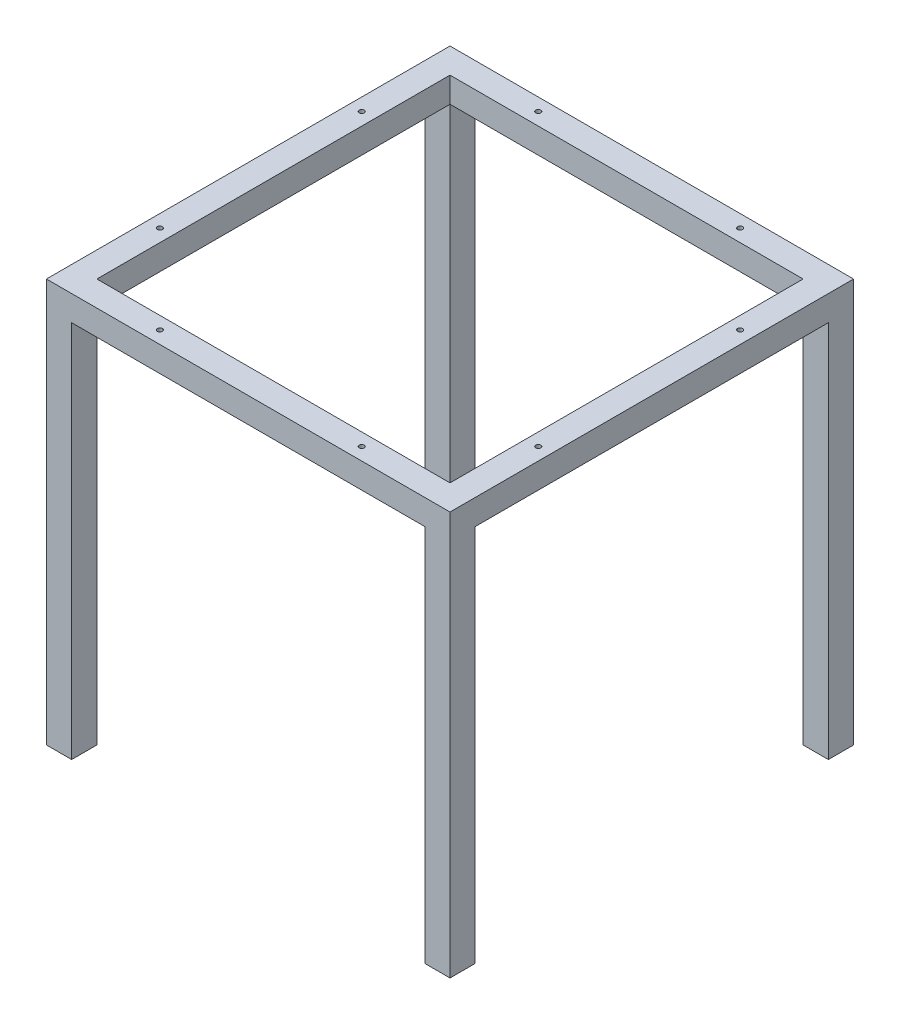
SolidWorks part; units mm, degrees
ref_plane "Front Plane" through (0, 0, 0) normal (0, 0, 1) x (1, 0, 0)
ref_plane "Top Plane" through (0, 0, 0) normal (0, 1, 0) x (1, 0, 0)
ref_plane "Right Plane" through (0, 0, 0) normal (1, 0, 0) x (0, 0, -1)
sketch "Sketch1" plane through (0, 0, 0) normal (0, 1, 0) x (1, 0, 0)
  line L1 (-400, -400) -> (400, -400)
  line L2 (-400, -400) -> (-400, 400)
  line L3 (-400, 400) -> (400, 400)
  line L4 (400, -400) -> (400, 400)
  line L5 (-400, -400) -> (400, 400) construction
  line L6 (-400, 400) -> (400, -400) construction
  line L7 (-350, 350) -> (350, 350)
  line L8 (-350, 350) -> (-350, -350)
  line L9 (-350, -350) -> (350, -350)
  line L10 (350, 350) -> (350, -350)
  point P0 (0, 0)
  dimension "D1" = 800
  dimension "D2" = 50
extrude "Boss-Extrude1" add sketch "Sketch1" along normal blind 50
sketch "Sketch2" plane through (0, 50, 0) normal (0, -1, 0) x (1, 0, 0)
  line L1 (-400, 400) -> (-350, 400)
  line L2 (-400, 400) -> (-400, 350)
  line L3 (-400, 350) -> (-350, 350)
  line L4 (-350, 400) -> (-350, 350)
  line L5 (400, 400) -> (350, 400)
  line L6 (400, 400) -> (400, 350)
  line L7 (400, 350) -> (350, 350)
  line L8 (350, 400) -> (350, 350)
  line L9 (400, -400) -> (350, -400)
  line L10 (400, -400) -> (400, -350)
  line L11 (400, -350) -> (350, -350)
  line L12 (350, -400) -> (350, -350)
  line L13 (-400, -400) -> (-350, -400)
  line L14 (-400, -400) -> (-400, -350)
  line L15 (-400, -350) -> (-350, -350)
  line L16 (-350, -400) -> (-350, -350)
  dimension "D1" = 50
extrude "Boss-Extrude2" add sketch "Sketch2" along normal blind 800
sketch "Sketch3" plane through (0, 50, 0) normal (0, 1, 0) x (1, 0, 0)
  line L0 (-400, 0) -> (-350, 0) construction
  line L1 (-400, 400) -> (-400, -400) construction
  line L2 (-350, 350) -> (-350, -350) construction
  line L3 (-375, 0) -> (-375, 200) construction
  line L4 (-375, 0) -> (-375, -200) construction
  line L5 (0, -350) -> (0, -400) construction
  line L6 (-350, -350) -> (350, -350) construction
  line L7 (-400, -400) -> (400, -400) construction
  line L8 (0, 350) -> (0, 400) construction
  line L9 (350, 350) -> (-350, 350) construction
  line L10 (400, 400) -> (-400, 400) construction
  line L11 (350, 0) -> (400, 0) construction
  line L12 (350, -350) -> (350, 350) construction
  line L13 (400, -400) -> (400, 400) construction
  line L14 (375, 0) -> (375, 200) construction
  line L15 (375, 0) -> (375, -200) construction
  line L16 (0, -375) -> (200, -375) construction
  line L17 (0, -375) -> (-200, -375) construction
  line L18 (0, 375) -> (-200, 375) construction
  line L19 (0, 375) -> (200, 375) construction
  circle A0 centre (-200, 375) radius 5
  circle A1 centre (-375, 200) radius 5
  circle A2 centre (-375, -200) radius 5
  circle A3 centre (-200, -375) radius 5
  circle A4 centre (200, -375) radius 5
  circle A5 centre (375, -200) radius 5
  circle A6 centre (375, 200) radius 5
  circle A7 centre (200, 375) radius 5
  dimension "D2" = 10
  dimension "D1" = 400
extrude "Cut-Extrude1" cut sketch "Sketch3" against normal through all both and the other way through all
